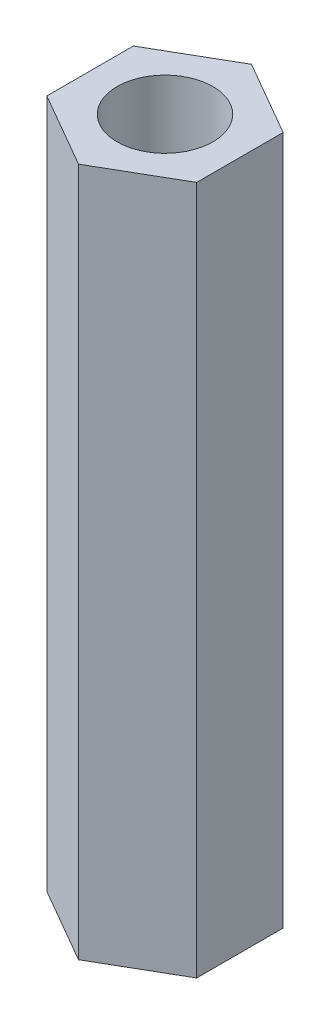
SolidWorks part; units mm, degrees
ref_plane "前视基准面" through (0, 0, 0) normal (0, 0, 1) x (1, 0, 0)
ref_plane "上视基准面" through (0, 0, 0) normal (0, 1, 0) x (1, 0, 0)
ref_plane "右视基准面" through (0, 0, 0) normal (1, 0, 0) x (0, 0, -1)
other "Configuration Table"
sketch "草图1" plane through (0, 0, 0) normal (0, 1, 0) x (1, 0, 0)
  line L0 (0.0741, 3.9248) -> (-2.4259, 2.4814)
  line L1 (-2.4259, 2.4814) -> (-2.4259, -0.4053)
  line L2 (-2.4259, -0.4053) -> (0.0741, -1.8487)
  line L3 (0.0741, -1.8487) -> (2.5741, -0.4053)
  line L4 (2.5741, -0.4053) -> (2.5741, 2.4814)
  line L5 (2.5741, 2.4814) -> (0.0741, 3.9248)
  circle A0 centre (0.0741, 1.038) radius 2.5 construction
  circle A1 centre (0.0741, 1.038) radius 1.6
  dimension "D1" = 3.2
  dimension "D2" = 5
extrude "凸台-拉伸1" add sketch "草图1" along normal blind 23
